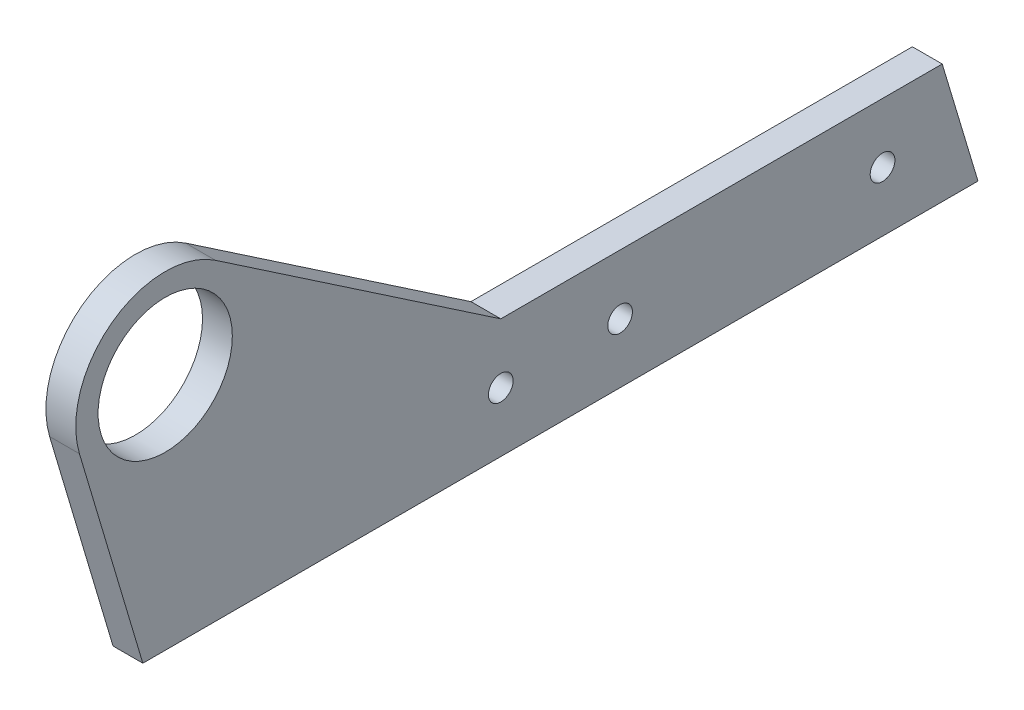
SolidWorks part; units mm, degrees
material "PC High Viscosity"
ref_plane "Front Plane" through (0, 0, 0) normal (0, 0, 1) x (1, 0, 0)
ref_plane "Top Plane" through (0, 0, 0) normal (0, 1, 0) x (1, 0, 0)
ref_plane "Right Plane" through (0, 0, 0) normal (1, 0, 0) x (0, 0, -1)
sketch "Sketch1" plane through (0, 0, 0) normal (1, 0, 0) x (0, 0, -1)
  line L0 (0, 0) -> (-84.1375, 0) construction
  line L1 (-84.1375, 0) -> (-84.1375, 38.1) construction
  line L2 (0, 0) -> (12.7, 0) construction
  line L3 (-12.7, 0) -> (-12.7, -12.7) construction
  line L4 (-88.9, -961.9) -> (-88.9, 49038.1) construction
  line L5 (-12.7, -12.7) -> (-88.9, -12.7)
  line L6 (-88.9, -12.7) -> (-102.3966, 32.668)
  line L7 (-12.7, 0) -> (-12.7, 12.7) construction
  line L8 (-12.7, 12.7) -> (-73.4504, 53.8699)
  line L9 (-12.7, 12.7) -> (25.4, 12.7)
  line L10 (-12.7, -12.7) -> (25.4, -12.7)
  line L12 (-1084.1375, 38.1) -> (48915.8625, 38.1) construction
  line L13 (-81.8955, 38.916) -> (46902.7355, 17139.9232) construction
  line L15 (25.4, -12.7) -> (88.9, -12.7)
  line L16 (88.9, -12.7) -> (81.28, 12.7)
  line L17 (25.4, 12.7) -> (81.28, 12.7)
  line L18 (-84.1375, 0) -> (-100.0125, 0) construction
  line L19 (12.7, 0) -> (68.58, 0) construction
  circle A0 centre (-84.1375, 38.1) radius 14.2875
  circle A1 centre (-12.7, 0) radius 2.6289
  circle A2 centre (12.7, 0) radius 2.6289
  arc A3 (-73.4504, 53.8699) -> (-102.3966, 32.668) centre (-84.1375, 38.1) ccw
  circle A7 centre (68.58, 0) radius 2.6289
  point P5 (-12.7, 0)
  point P12 (136.6433, 118.4576)
  dimension "D3" = 28.575
  dimension "D6" = 5.2578
  dimension "D7" = 5.2578
  dimension "D9" = 38.1
  dimension "D15" = 55.88
  dimension "D18" = 5.2578
  dimension "D1" = 84.1375
  dimension "D2" = 38.1
  dimension "D4" = 12.7
  dimension "D5" = 12.7
  dimension "D8" = 12.7
  dimension "D10" = 12.7
  dimension "D11" = 38.1
  dimension "D12" = 20
  dimension "D13" = 15.875
  dimension "D16" = 63.5
  dimension "D17" = 76.2
  dimension "D19" = 12.7
extrude "Boss-Extrude1" add sketch "Sketch1" along normal blind 6.35
